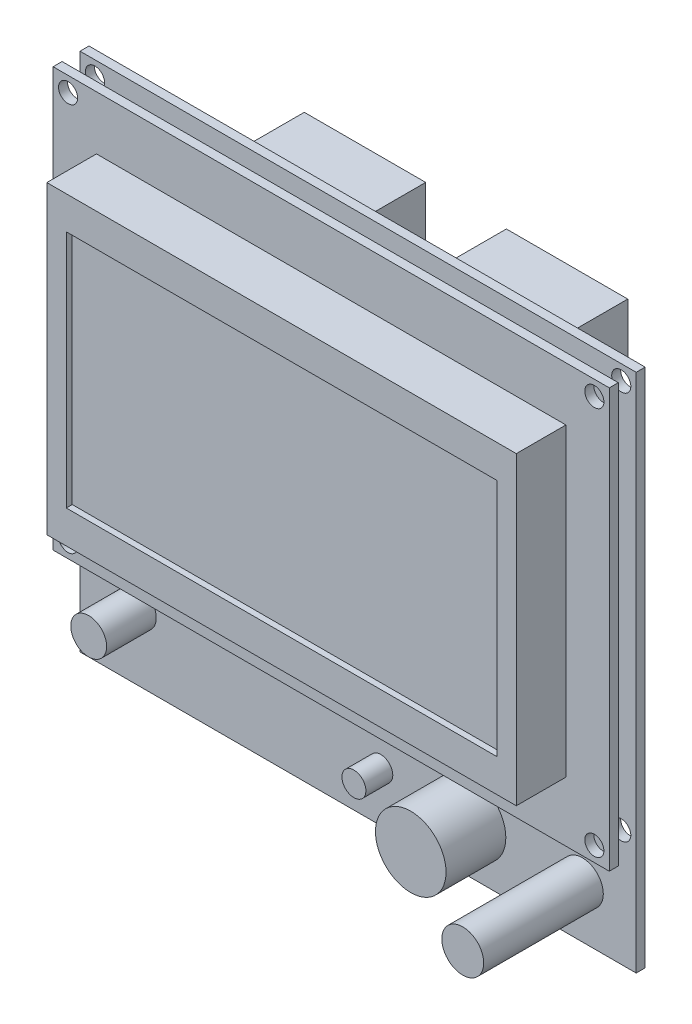
SolidWorks part; units mm, degrees
ref_plane "Plano frontal" through (0, 0, 0) normal (0, 0, 1) x (1, 0, 0)
ref_plane "Plano superior" through (0, 0, 0) normal (0, 1, 0) x (1, 0, 0)
ref_plane "Plano direito" through (0, 0, 0) normal (1, 0, 0) x (0, 0, -1)
sketch "Esboço1" plane through (0, 0, 0) normal (0, 0, 1) x (1, 0, 0)
  line L1 (-46.5, 43.5) -> (46.5, 43.5)
  line L2 (-46.5, 43.5) -> (-46.5, -43.5)
  line L3 (-46.5, -43.5) -> (46.5, -43.5)
  line L4 (46.5, 43.5) -> (46.5, -43.5)
  line L5 (-46.5, 43.5) -> (46.5, -43.5) construction
  line L6 (-46.5, -43.5) -> (46.5, 43.5) construction
  point P0 (0, 0)
  dimension "D1" = 93
  dimension "D2" = 87
extrude "Ressalto-extrusão1" add sketch "Esboço1" along normal blind 1.5
sketch "Esboço3" plane through (0, 0, 1.5) normal (0, 0, 1) x (1, 0, 0)
  line L0 (46.5, -43.5) -> (46.5, 43.5) construction
  line L1 (-46.5, 43.5) -> (46.5, 43.5)
  line L2 (-46.5, 43.5) -> (-46.5, -26.5)
  line L3 (-46.5, -26.5) -> (46.5, -26.5)
  line L4 (46.5, 43.5) -> (46.5, -26.5)
  line L5 (-46.5, 43.5) -> (46.5, -26.5) construction
  line L6 (-46.5, -26.5) -> (46.5, 43.5) construction
  line L7 (-46.5, 43.5) -> (-46.5, -43.5) construction
  line L8 (46.5, 43.5) -> (-46.5, 43.5) construction
  point P0 (0, 8.5)
  dimension "D1" = 70
extrude "Ressalto-extrusão2" add sketch "Esboço3" along normal blind 1.5 from offset 3 separate body
sketch "Esboço4" plane through (0, 0, 6) normal (0, 0, 1) x (1, 0, 0)
  line L0 (46.5, 43.5) -> (-46.5, 43.5) construction
  line L1 (-39.25, 34.5) -> (39.25, 34.5)
  line L2 (-39.25, 34.5) -> (-39.25, -16.5)
  line L3 (-39.25, -16.5) -> (39.25, -16.5)
  line L4 (39.25, 34.5) -> (39.25, -16.5)
  line L5 (-39.25, 34.5) -> (39.25, -16.5) construction
  line L6 (-39.25, -16.5) -> (39.25, 34.5) construction
  point P0 (0, 9)
  point P7 (0, 0)
  dimension "D1" = 51
  dimension "D2" = 78.5
  dimension "D3" = 9
extrude "Ressalto-extrusão3" add sketch "Esboço4" along normal blind 8.3
sketch "Esboço5" plane through (0, 0, 14.3) normal (0, 0, 1) x (1, 0, 0)
  line L0 (39.25, -16.5) -> (39.25, 34.5) construction
  line L1 (-36, 29) -> (36, 29)
  line L2 (-36, 29) -> (-36, -11)
  line L3 (-36, -11) -> (36, -11)
  line L4 (36, 29) -> (36, -11)
  line L5 (-36, 29) -> (36, -11) construction
  line L6 (-36, -11) -> (36, 29) construction
  line L7 (39.25, 34.5) -> (-39.25, 34.5) construction
  point P0 (0, 9)
  point P7 (39.25, 9)
  point P8 (0, 0)
  point P11 (0, 34.5)
  dimension "D1" = 72
  dimension "D2" = 40
extrude "Corte-extrusão1" cut sketch "Esboço5" against normal blind 1
sketch "Esboço6" plane through (0, 0, 1.5) normal (0, 0, 1) x (1, 0, 0)
  line L0 (46.5, -43.5) -> (46.5, 43.5) construction
  line L1 (-46.5, -43.5) -> (46.5, -43.5) construction
  circle A0 centre (37.5, -34.8) radius 3.5
  dimension "D3" = 7
  dimension "D1" = 9
  dimension "D2" = 8.7
extrude "Ressalto-extrusão4" add sketch "Esboço6" along normal blind 20
sketch "Esboço7" plane through (0, 0, 1.5) normal (0, 0, 1) x (1, 0, 0)
  line L0 (46.5, -43.5) -> (46.5, 43.5) construction
  line L1 (-46.5, -43.5) -> (46.5, -43.5) construction
  circle A0 centre (3.8, -35.2) radius 2
  point P2 (0, 0)
  dimension "D3" = 4
  dimension "D1" = 42.7
  dimension "D2" = 8.3
extrude "Ressalto-extrusão5" add sketch "Esboço7" along normal blind 4.5
sketch "Esboço8" plane through (0, 0, 1.5) normal (0, 0, 1) x (1, 0, 0)
  line L0 (-46.5, -43.5) -> (46.5, -43.5) construction
  line L1 (46.5, -43.5) -> (46.5, 43.5) construction
  circle A0 centre (18.8, -34.8) radius 5.9
  dimension "D3" = 11.8
  dimension "D1" = 8.7
  dimension "D2" = 27.7
extrude "Ressalto-extrusão6" add sketch "Esboço8" along normal blind 10
sketch "Esboço9" plane through (0, 0, 1.5) normal (0, 0, 1) x (1, 0, 0)
  line L0 (-46.5, 43.5) -> (-46.5, -43.5) construction
  line L1 (-46.5, -43.5) -> (46.5, -43.5) construction
  circle A0 centre (-36.75, -32.2) radius 3
  dimension "D3" = 6
  dimension "D1" = 9.75
  dimension "D2" = 11.3
extrude "Ressalto-extrusão7" add sketch "Esboço9" along normal blind 8.3
sketch "Esboço10" plane through (0, 0, 6) normal (0, 0, 1) x (1, 0, 0)
  line L0 (46.5, 43.5) -> (-46.5, 43.5) construction
  line L1 (0, 0) -> (0, 41) construction
  circle A0 centre (-44, 41) radius 1.6
  circle A1 centre (44, 41) radius 1.6
  circle A2 centre (44, -24) radius 1.6
  circle A3 centre (-44, -24) radius 1.6
  point P6 (0, 0)
  dimension "D1" = 3.2
  dimension "D2" = 2.5
  dimension "D3" = 88
  dimension "D4" = 65
extrude "Corte-extrusão2" cut sketch "Esboço10" against normal through all both and the other way through all
sketch "Esboço11" plane through (0, 0, 0) normal (0, 0, -1) x (-1, 0, 0)
  line L0 (-46.5, 43.5) -> (46.5, 43.5) construction
  line L1 (-28.5887, 36.9) -> (-8.2887, 36.9)
  line L2 (-28.5887, 36.9) -> (-28.5887, 28.3)
  line L3 (-28.5887, 28.3) -> (-8.2887, 28.3)
  line L4 (-8.2887, 36.9) -> (-8.2887, 28.3)
  line L5 (-28.5887, 36.9) -> (-8.2887, 28.3) construction
  line L6 (-28.5887, 28.3) -> (-8.2887, 36.9) construction
  line L7 (5.2, 36.9) -> (25.5, 36.9)
  line L8 (5.2, 36.9) -> (5.2, 28.3)
  line L9 (5.2, 28.3) -> (25.5, 28.3)
  line L10 (25.5, 36.9) -> (25.5, 28.3)
  line L11 (5.2, 36.9) -> (25.5, 28.3) construction
  line L12 (5.2, 28.3) -> (25.5, 36.9) construction
  line L13 (46.5, 43.5) -> (46.5, -43.5) construction
  point P0 (-18.4387, 32.6)
  point P5 (15.35, 32.6)
  dimension "D1" = 13.4887
  dimension "D2" = 6.6
  dimension "D3" = 20.3
  dimension "D4" = 21
  dimension "D5" = 8.6
extrude "Ressalto-extrusão8" add sketch "Esboço11" along normal blind 15
sketch "Esboço12" plane through (0, 0, 0) normal (0, 0, -1) x (-1, 0, 0)
  line L0 (46.5, 43.5) -> (46.5, -43.5) construction
  line L1 (46.4, 21.5) -> (20.9, 21.5)
  line L2 (46.4, 21.5) -> (46.4, -5)
  line L3 (46.4, -5) -> (20.9, -5)
  line L4 (20.9, 21.5) -> (20.9, -5)
  line L5 (-46.5, 43.5) -> (46.5, 43.5) construction
  dimension "D1" = 26.5
  dimension "D2" = 25.5
  dimension "D3" = 0.1
  dimension "D4" = 22
extrude "Ressalto-extrusão9" add sketch "Esboço12" along normal blind 3
